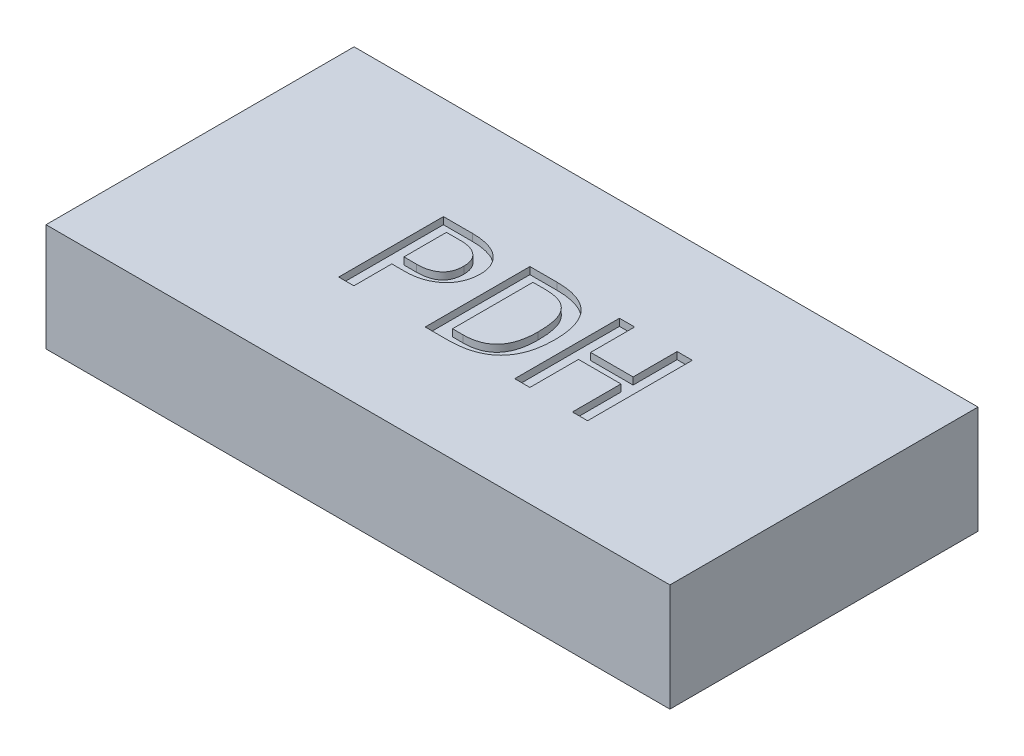
SolidWorks part; units mm, degrees
ref_plane "Front Plane" through (0, 0, 0) normal (0, 0, 1) x (1, 0, 0)
ref_plane "Top Plane" through (0, 0, 0) normal (0, 1, 0) x (1, 0, 0)
ref_plane "Right Plane" through (0, 0, 0) normal (1, 0, 0) x (0, 0, -1)
sketch "Sketch1" plane through (0, 0, 0) normal (0, 1, 0) x (1, 0, 0)
  line L1 (0, 0) -> (224.79, 0)
  line L2 (0, 0) -> (0, 110.998)
  line L3 (0, 110.998) -> (224.79, 110.998)
  line L4 (224.79, 0) -> (224.79, 110.998)
  dimension "D1" = 110.998
  dimension "D2" = 224.79
extrude "Boss-Extrude1" add sketch "Sketch1" along normal mid plane 38.7731
sketch "Sketch2" plane through (0, 19.3865, 0) normal (0, 1, 0) x (1, 0, 0)
  text T0 "PDH\r\n" font "Consolas" height in points 144
extrude "Cut-Extrude1" cut sketch "Sketch2" against normal blind 2.54
